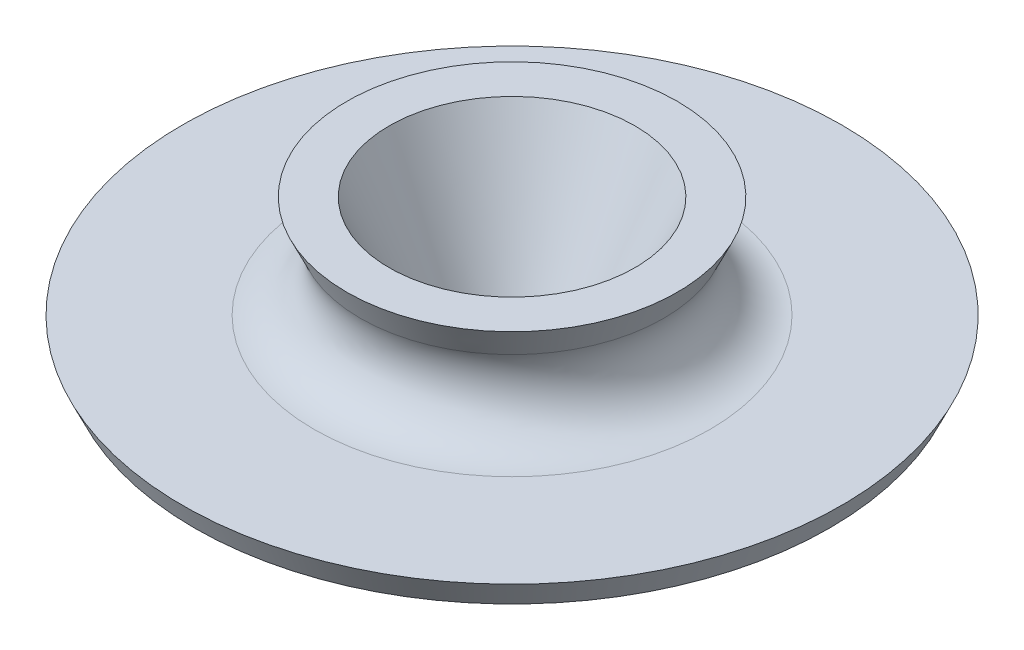
SolidWorks part; units mm, degrees
ref_plane "Front Plane" through (0, 0, 0) normal (0, 0, 1) x (1, 0, 0)
ref_plane "Top Plane" through (0, 0, 0) normal (0, 1, 0) x (1, 0, 0)
ref_plane "Right Plane" through (0, 0, 0) normal (1, 0, 0) x (0, 0, -1)
sketch "Sketch1" plane through (0, 0, 0) normal (0, 0, 1) x (1, 0, 0)
  line L0 (0, 0) -> (0, 97.7001) construction
  line L8 (-12.7, -0.5717) -> (-30.4663, 37.5283)
  line L9 (-12.7, -0.5717) -> (-19.05, -0.5717)
  line L10 (-19.05, -0.5717) -> (-22.0111, 5.7783)
  line L11 (-22.0111, 5.7783) -> (-78.7191, 5.7783)
  line L12 (-78.7191, 5.7783) -> (-81.6802, 12.1283)
  line L13 (-81.6802, 12.1283) -> (-50.1907, 12.1283)
  line L14 (-50.1907, 12.1283) -> (-29.1318, 12.1283)
  line L15 (-29.1318, 12.1283) -> (-40.976, 37.5283)
  line L16 (-40.976, 37.5283) -> (-30.4663, 37.5283)
  dimension "D1" = 25
  dimension "D7" = 6.35
  dimension "D2" = 6.35
  dimension "D3" = 25.4
  dimension "D4" = 57.15
  dimension "D5" = 9.525
  dimension "D6" = 38.1
  dimension "D8" = 6.35
revolve "Revolve2" add sketch "Sketch1" angle 360 about L0
fillet "Fillet2" radius 12.7 1 edges at (0, 12.1283, -29.1318)
fillet "Fillet3" radius 2.54 1 edges at (0, 5.7783, -22.0111)
